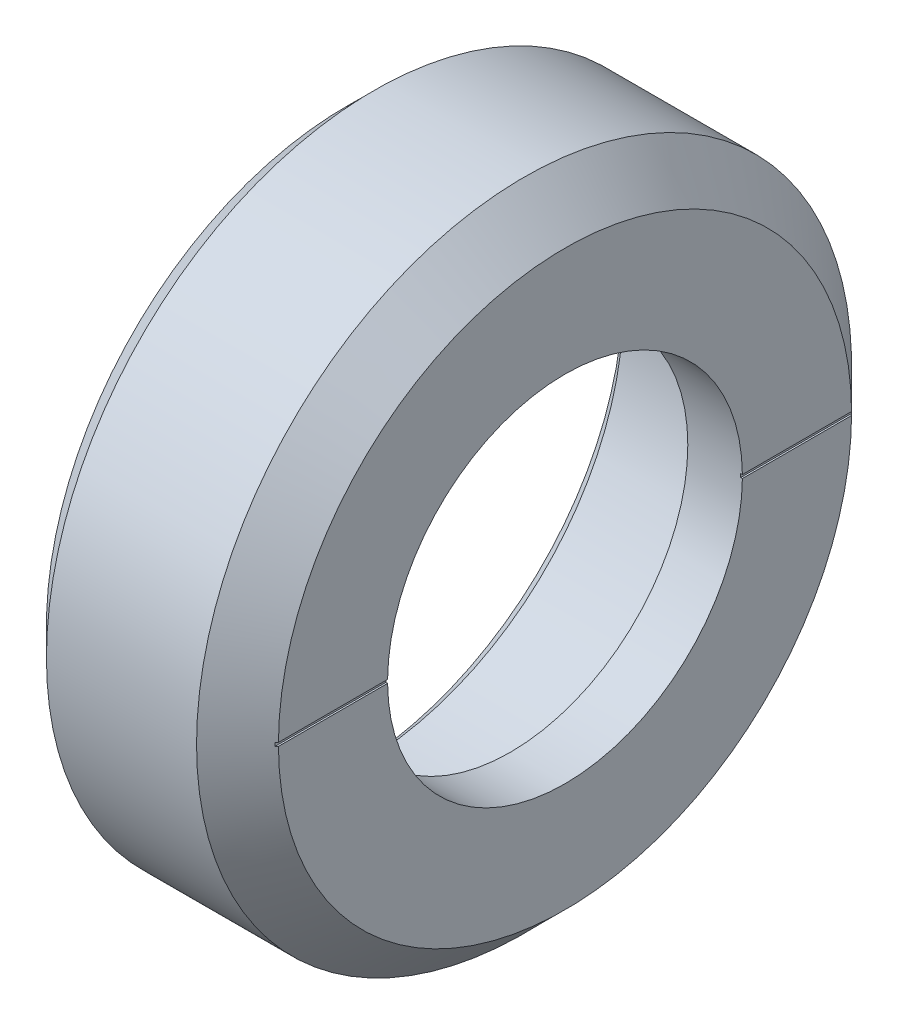
SolidWorks part; units mm, degrees
ref_plane "Plan1" through (0, 0, 0) normal (0, 0, 1) x (1, 0, 0)
ref_plane "Plan2" through (0, 0, 0) normal (0, 1, 0) x (1, 0, 0)
ref_plane "Plan3" through (0, 0, 0) normal (1, 0, 0) x (0, 0, -1)
sketch "Esquisse1" plane through (0, 0, 0) normal (0, 0, 1) x (1, 0, 0)
  line L0 (0, 0) -> (20, 0) construction
  line L1 (0, 19.25) -> (0, 24)
  line L2 (0, 24) -> (16, 24)
  line L3 (16, 24) -> (16, 13)
  line L4 (16, 13) -> (12, 13)
  line L5 (12, 13) -> (12, 20.25)
  line L6 (12, 20.25) -> (11, 20.25)
  line L7 (11, 20.25) -> (11, 19.25)
  line L8 (11, 19.25) -> (0, 19.25)
  dimension "D1" = 24
  dimension "D2" = 13
  dimension "D3" = 19.25
  dimension "D4" = 1
  dimension "D5" = 16
  dimension "D6" = 1
  dimension "D7" = 12
revolve "Base-Révolution" add sketch "Esquisse1"
cosmetic thread "Représentation de filetage1"
chamfer "Chanfrein3" distance 1 angle 45 1 edges at (0, 0, 19.25)
chamfer "Chanfrein1" distance 3 angle 45 1 edges at (16, 0, 24)
chamfer "Chanfrein2" distance 2 angle 45 1 edges at (0, 0, 24)
sketch "Esquisse2" plane through (0, 0, 0) normal (0, 0, 1) x (1, 0, 0)
  line L0 (0, 0) -> (20, 0) construction
  line L1 (16, -21) -> (16, 21) construction
  line L2 (18, 0.125) -> (15.875, 0.125)
  line L3 (18, 0.125) -> (18, -0.125)
  line L4 (18, -0.125) -> (15.875, -0.125)
  line L5 (15.875, 0.125) -> (15.875, -0.125)
  line L6 (16, -21) -> (16, 21) construction
  dimension "D1" = 0.25
  dimension "D2" = 2
  dimension "D3" = 0.25
extrude "Enlèv. mat.-Extru.1" cut sketch "Esquisse2" along normal mid plane 83
